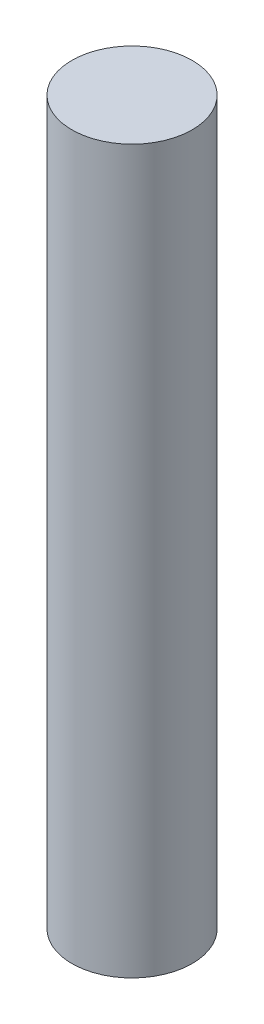
SolidWorks part; units mm, degrees
ref_plane "Front Plane" through (0, 0, 0) normal (0, 0, 1) x (1, 0, 0)
ref_plane "Top Plane" through (0, 0, 0) normal (0, 1, 0) x (1, 0, 0)
ref_plane "Right Plane" through (0, 0, 0) normal (1, 0, 0) x (0, 0, -1)
sketch "Sketch1" plane through (0, 0, 0) normal (0, 1, 0) x (1, 0, 0)
  circle A0 centre (0, 0) radius 6.35
  dimension "D1" = 12.7
extrude "Boss-Extrude1" add sketch "Sketch1" along normal blind 76.2 contours A0
